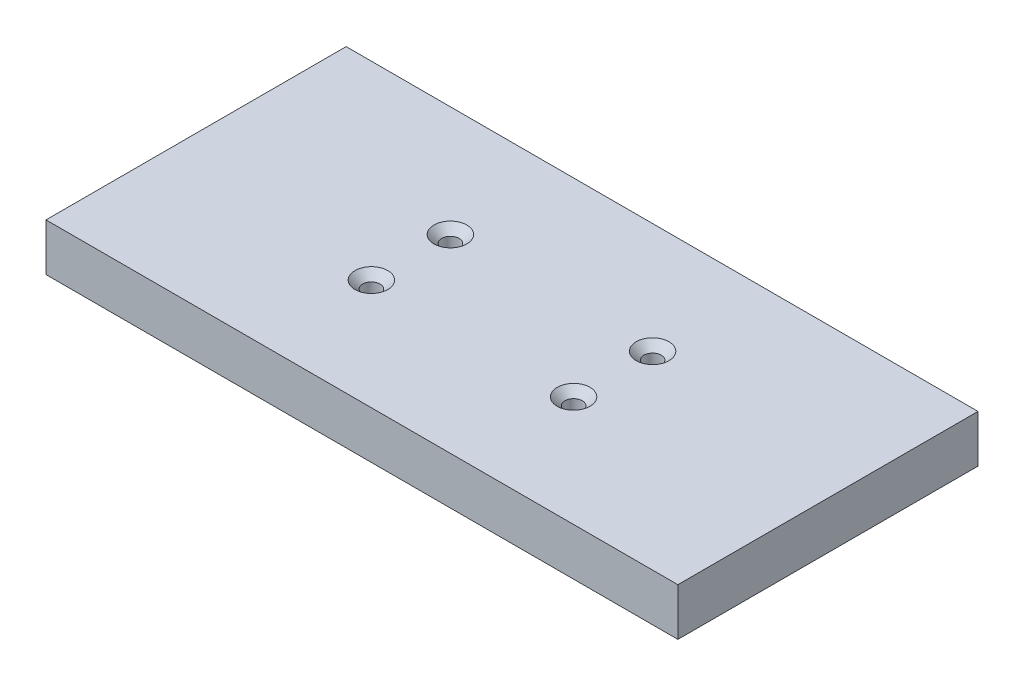
SolidWorks part; units mm, degrees
ref_plane "Front Plane" through (0, 0, 0) normal (0, 0, 1) x (1, 0, 0)
ref_plane "Top Plane" through (0, 0, 0) normal (0, 1, 0) x (1, 0, 0)
ref_plane "Right Plane" through (0, 0, 0) normal (1, 0, 0) x (0, 0, -1)
sketch "Sketch1" plane through (0, 0, 0) normal (0, 1, 0) x (1, 0, 0)
  line L1 (-100, -47.5) -> (100, -47.5)
  line L2 (-100, -47.5) -> (-100, 47.5)
  line L3 (-100, 47.5) -> (100, 47.5)
  line L4 (100, -47.5) -> (100, 47.5)
  line L5 (-100, -47.5) -> (100, 47.5) construction
  line L6 (-100, 47.5) -> (100, -47.5) construction
  point P0 (0, 0)
  dimension "D1" = 95
  dimension "D2" = 200
extrude "Boss-Extrude1" add sketch "Sketch1" along normal blind 15
sketch "Sketch2" plane through (0, 15, 0) normal (0, 1, 0) x (1, 0, 0)
  line L0 (-100, 0) -> (100, 0) construction
  line L1 (-100, 47.5) -> (-100, -47.5) construction
  line L2 (100, -47.5) -> (100, 47.5) construction
  line L3 (0, 47.5) -> (0, -47.5) construction
  line L4 (100, 47.5) -> (-100, 47.5) construction
  line L5 (-100, -47.5) -> (100, -47.5) construction
hole_wizard "CSK for M5 Cross Recess Flat Head Screw2" positions "Sketch8" profile "Sketch9" countersink size "M5" standard "IS" end condition through all
sketch "Sketch8" plane through (0, 15, 0) normal (0, 1, 0) x (1, 0, 0)
  line L0 (100, -47.5) -> (100, 47.5) construction
  line L1 (100, 47.5) -> (-100, 47.5) construction
  line L3 (100, 0) -> (-100, 0) construction
  line L4 (0, -47.5) -> (0, 47.5) construction
  point P0 (32, 12.5)
  point P21 (32, -12.5)
  point P29 (-32, -12.5)
  point P30 (-32, 12.5)
  dimension "D1" = 68
  dimension "D2" = 35
sketch "Sketch9" plane through (32, 15, -12.5) normal (1, 0, 0) x (0, 0, 1)
  line L0 (0, 0) -> (0, 15)
  line L1 (0, 15) -> (2.75, 15)
  line L2 (2.75, 15) -> (2.75, 2.45)
  line L3 (2.75, 2.45) -> (5.2, 0)
  line L5 (5.2, 0) -> (0, 0)
  line L6 (-2.75, 2.45) -> (-5.2, 0) construction
  line L11 (0, -6.35) -> (0, 107.95) construction
  dimension "Thru Hole Dia." = 5.5
  dimension "Thru Hole Depth" = 15
  dimension "Near C'Sink Dia." = 10.4
  dimension "Near C'Sink Angle" = 90
